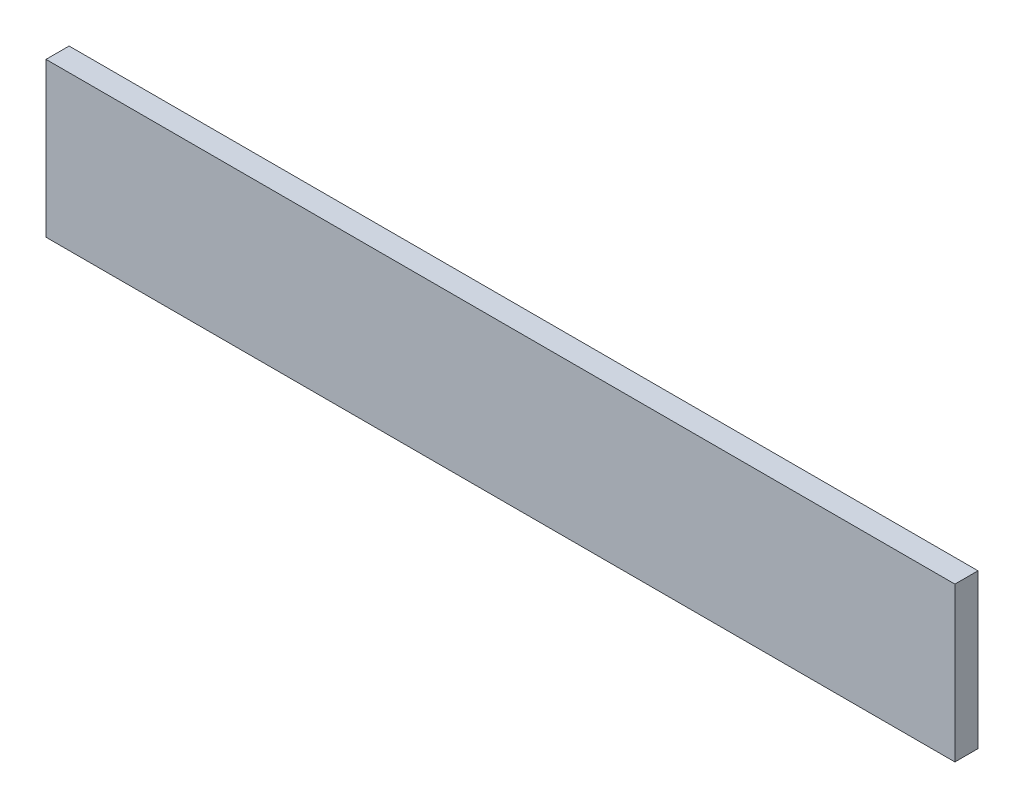
SolidWorks part; units mm, degrees
material "Pine"
ref_plane "Front Plane" through (0, 0, 0) normal (0, 0, 1) x (1, 0, 0)
ref_plane "Top Plane" through (0, 0, 0) normal (0, 1, 0) x (1, 0, 0)
ref_plane "Right Plane" through (0, 0, 0) normal (1, 0, 0) x (0, 0, -1)
sketch "Sketch1" plane through (0, 0, 0) normal (1, 0, 0) x (0, 0, -1)
  line L1 (-7.8921, 36.8754) -> (11.1579, 36.8754)
  line L2 (-7.8921, 36.8754) -> (-7.8921, -90.1246)
  line L3 (-7.8921, -90.1246) -> (11.1579, -90.1246)
  line L4 (11.1579, 36.8754) -> (11.1579, -90.1246)
  dimension "D1" = 19.05
  dimension "D2" = 127
extrude "Boss-Extrude1" add sketch "Sketch1" along normal blind 749.3
